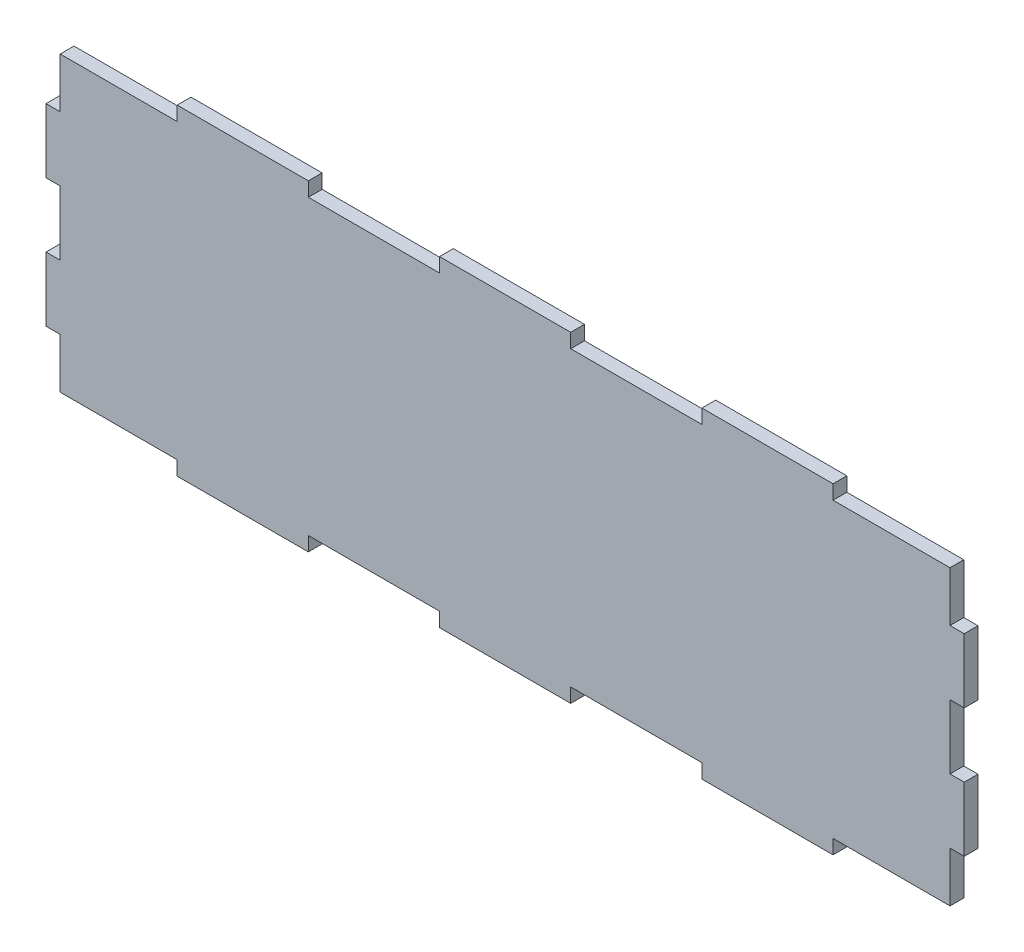
SolidWorks part; units mm, degrees
ref_plane "Alzado" through (0, 0, 0) normal (0, 0, 1) x (1, 0, 0)
ref_plane "Planta" through (0, 0, 0) normal (0, 1, 0) x (1, 0, 0)
ref_plane "Vista lateral" through (0, 0, 0) normal (1, 0, 0) x (0, 0, -1)
sketch "Croquis1" plane through (0, 0, 0) normal (0, 0, 1) x (1, 0, 0)
  line L0 (100, 0) -> (-100, 0) construction
  line L1 (-100, -35) -> (100, -35)
  line L2 (-100, -35) -> (-100, 35)
  line L3 (-100, 35) -> (100, 35)
  line L4 (100, -35) -> (100, 35)
  line L5 (-100, -35) -> (100, 35) construction
  line L6 (-100, 35) -> (100, -35) construction
  line L7 (-100, 35) -> (-71.4286, 35)
  line L8 (-100, 35) -> (-100, 31.9)
  line L9 (-100, 31.9) -> (-71.4286, 31.9)
  line L10 (-71.4286, 35) -> (-71.4286, 31.9)
  line L11 (-42.8571, 35) -> (-14.2857, 35)
  line L12 (-42.8571, 35) -> (-42.8571, 31.9)
  line L13 (-42.8571, 31.9) -> (-14.2857, 31.9)
  line L14 (-14.2857, 35) -> (-14.2857, 31.9)
  line L15 (14.2857, 35) -> (42.8571, 35)
  line L16 (14.2857, 35) -> (14.2857, 31.9)
  line L17 (14.2857, 31.9) -> (42.8571, 31.9)
  line L18 (42.8571, 35) -> (42.8571, 31.9)
  line L19 (71.4286, 35) -> (100, 35)
  line L20 (71.4286, 35) -> (71.4286, 31.9)
  line L21 (71.4286, 31.9) -> (100, 31.9)
  line L22 (100, 35) -> (100, 31.9)
  line L23 (0, 35) -> (0, -35) construction
  line L24 (-100, -35) -> (-96.9, -35)
  line L25 (-100, -35) -> (-100, -21)
  line L26 (-100, -21) -> (-96.9, -21)
  line L27 (-96.9, -35) -> (-96.9, -21)
  line L28 (-100, -7) -> (-96.9, -7)
  line L29 (-100, -7) -> (-100, 7)
  line L30 (-100, 7) -> (-96.9, 7)
  line L31 (-96.9, -7) -> (-96.9, 7)
  line L32 (-100, 21) -> (-96.9, 21)
  line L33 (-100, 21) -> (-100, 35)
  line L34 (-100, 35) -> (-96.9, 35)
  line L35 (-96.9, 21) -> (-96.9, 35)
  line L36 (100, -21) -> (96.9, -21)
  line L37 (96.9, -35) -> (96.9, -21)
  line L38 (100, -35) -> (96.9, -35)
  line L39 (100, -35) -> (100, -21)
  line L40 (100, 7) -> (96.9, 7)
  line L41 (96.9, -7) -> (96.9, 7)
  line L42 (100, -7) -> (96.9, -7)
  line L43 (100, -7) -> (100, 7)
  line L44 (100, 35) -> (96.9, 35)
  line L45 (96.9, 21) -> (96.9, 35)
  line L46 (100, 21) -> (96.9, 21)
  line L47 (100, 21) -> (100, 35)
  line L48 (71.4286, -31.9) -> (100, -31.9)
  line L49 (100, -35) -> (100, -31.9)
  line L50 (71.4286, -35) -> (100, -35)
  line L51 (71.4286, -35) -> (71.4286, -31.9)
  line L52 (14.2857, -31.9) -> (42.8571, -31.9)
  line L53 (42.8571, -35) -> (42.8571, -31.9)
  line L54 (14.2857, -35) -> (42.8571, -35)
  line L55 (14.2857, -35) -> (14.2857, -31.9)
  line L56 (-100, -31.9) -> (-71.4286, -31.9)
  line L57 (-71.4286, -35) -> (-71.4286, -31.9)
  line L58 (-100, -35) -> (-71.4286, -35)
  line L59 (-100, -35) -> (-100, -31.9)
  line L60 (-42.8571, -31.9) -> (-14.2857, -31.9)
  line L61 (-14.2857, -35) -> (-14.2857, -31.9)
  line L62 (-42.8571, -35) -> (-14.2857, -35)
  line L63 (-42.8571, -35) -> (-42.8571, -31.9)
  point P0 (0, 0)
  point P46 (-131.137, 15.9396)
  dimension "D2" = 70
  dimension "D3" = 28.5714
  dimension "D4" = 28.5714
  dimension "D5" = 28.5714
  dimension "D6" = 28.5714
  dimension "D7" = 28.5714
  dimension "D8" = 28.5714
  dimension "D9" = 28.5714
  dimension "D10" = 3.1
  dimension "D11" = 14
  dimension "D12" = 14
  dimension "D13" = 14
  dimension "D14" = 14
  dimension "D15" = 14
  dimension "D16" = 3.1
extrude "Saliente-Extruir2" add sketch "Croquis1" along normal blind 3 contours L4 L46 L45 L21 L20 L3 L18 L17 L16 L14 L13 L12 L10 L9 L35 L32 L2 L30 L31 L28 L26 L27 L1 L37 L36 L42 L41 L40
